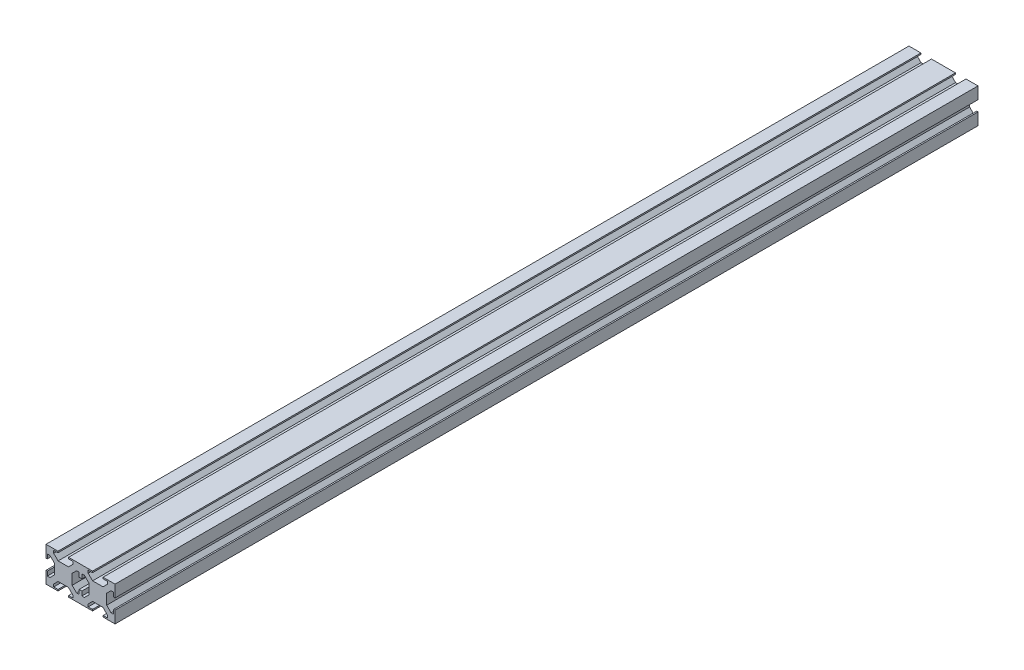
SolidWorks part; units mm, degrees
ref_plane "前视基准面" through (0, 0, 0) normal (0, 0, 1) x (1, 0, 0)
ref_plane "上视基准面" through (0, 0, 0) normal (0, 1, 0) x (1, 0, 0)
ref_plane "右视基准面" through (0, 0, 0) normal (1, 0, 0) x (0, 0, -1)
sketch "草图1" plane through (0, 0, 0) normal (0, 0, 1) x (1, 0, 0)
  line L0 (30, 10) -> (10, -10) construction
  line L1 (-10, -10) -> (30, -10)
  line L2 (-10, -10) -> (-10, 10)
  line L3 (-10, 10) -> (30, 10)
  line L4 (10, -10) -> (10, 10) construction
  line L5 (-10, -10) -> (10, 10) construction
  line L6 (-10, 10) -> (10, -10) construction
  line L7 (30, -10) -> (10, 10) construction
  line L8 (30, -10) -> (30, 10)
  line L9 (-3.05, 10) -> (-3.05, 9.2)
  line L10 (-3.05, 9.2) -> (-5.55, 9.2)
  line L11 (-5.55, 9.2) -> (-5.55, 7.7)
  line L12 (-5.55, 7.7) -> (-3, 5.15)
  line L13 (-3, 5.15) -> (3, 5.15)
  line L14 (0, -1000) -> (0, 49000) construction
  line L15 (-1000, 0) -> (49000, 0) construction
  line L16 (5.55, 7.7) -> (3, 5.15)
  line L17 (5.55, 9.2) -> (5.55, 7.7)
  line L18 (3.05, 9.2) -> (5.55, 9.2)
  line L19 (3.05, 10) -> (3.05, 9.2)
  line L20 (10, 3.05) -> (9.2, 3.05)
  line L21 (9.2, 3.05) -> (9.2, 5.55)
  line L22 (9.2, 5.55) -> (7.7, 5.55)
  line L23 (7.7, 5.55) -> (5.15, 3)
  line L24 (5.15, 3) -> (5.15, -3)
  line L25 (7.7, -5.55) -> (5.15, -3)
  line L26 (9.2, -5.55) -> (7.7, -5.55)
  line L27 (9.2, -3.05) -> (9.2, -5.55)
  line L28 (10, -3.05) -> (9.2, -3.05)
  line L29 (3.05, -10) -> (3.05, -9.2)
  line L30 (3.05, -9.2) -> (5.55, -9.2)
  line L31 (5.55, -9.2) -> (5.55, -7.7)
  line L32 (5.55, -7.7) -> (3, -5.15)
  line L33 (3, -5.15) -> (-3, -5.15)
  line L34 (-5.55, -7.7) -> (-3, -5.15)
  line L35 (-5.55, -9.2) -> (-5.55, -7.7)
  line L36 (-3.05, -9.2) -> (-5.55, -9.2)
  line L37 (-3.05, -10) -> (-3.05, -9.2)
  line L38 (-10, -3.05) -> (-9.2, -3.05)
  line L39 (-9.2, -3.05) -> (-9.2, -5.55)
  line L40 (-9.2, -5.55) -> (-7.7, -5.55)
  line L41 (-7.7, -5.55) -> (-5.15, -3)
  line L42 (-5.15, -3) -> (-5.15, 3)
  line L43 (-7.7, 5.55) -> (-5.15, 3)
  line L44 (-9.2, 5.55) -> (-7.7, 5.55)
  line L45 (-9.2, 3.05) -> (-9.2, 5.55)
  line L46 (-10, 3.05) -> (-9.2, 3.05)
  line L47 (30, 3.05) -> (29.2, 3.05)
  line L48 (29.2, 3.05) -> (29.2, 5.55)
  line L49 (29.2, 5.55) -> (27.7, 5.55)
  line L50 (27.7, 5.55) -> (25.15, 3)
  line L51 (25.15, -3) -> (25.15, 3)
  line L52 (27.7, -5.55) -> (25.15, -3)
  line L53 (29.2, -5.55) -> (27.7, -5.55)
  line L54 (29.2, -3.05) -> (29.2, -5.55)
  line L55 (30, -3.05) -> (29.2, -3.05)
  line L56 (23.05, -10) -> (23.05, -9.2)
  line L57 (23.05, -9.2) -> (25.55, -9.2)
  line L58 (25.55, -9.2) -> (25.55, -7.7)
  line L59 (25.55, -7.7) -> (23, -5.15)
  line L60 (17, -5.15) -> (23, -5.15)
  line L61 (14.45, -7.7) -> (17, -5.15)
  line L62 (14.45, -9.2) -> (14.45, -7.7)
  line L63 (16.95, -9.2) -> (14.45, -9.2)
  line L64 (16.95, -10) -> (16.95, -9.2)
  line L65 (10, -3.05) -> (10.8, -3.05)
  line L66 (10.8, -3.05) -> (10.8, -5.55)
  line L67 (10.8, -5.55) -> (12.3, -5.55)
  line L68 (12.3, -5.55) -> (14.85, -3)
  line L69 (14.85, 3) -> (14.85, -3)
  line L70 (12.3, 5.55) -> (14.85, 3)
  line L71 (10.8, 5.55) -> (12.3, 5.55)
  line L72 (10.8, 3.05) -> (10.8, 5.55)
  line L73 (10, 3.05) -> (10.8, 3.05)
  line L74 (16.95, 10) -> (16.95, 9.2)
  line L75 (16.95, 9.2) -> (14.45, 9.2)
  line L76 (14.45, 9.2) -> (14.45, 7.7)
  line L77 (14.45, 7.7) -> (17, 5.15)
  line L78 (23, 5.15) -> (17, 5.15)
  line L79 (25.55, 7.7) -> (23, 5.15)
  line L80 (25.55, 9.2) -> (25.55, 7.7)
  line L81 (23.05, 9.2) -> (25.55, 9.2)
  line L82 (23.05, 10) -> (23.05, 9.2)
  point P0 (0, 0)
  point P8 (20, 0)
  point P20 (0, 5.15)
  point P24 (25.15, 0)
  point P34 (5.15, 0)
  point P45 (0, -5.15)
  point P56 (-5.15, 0)
  point P60 (0, 0)
  point P72 (20, -5.15)
  point P83 (14.85, 0)
  point P94 (20, 5.15)
  point P105 (20, 0)
  dimension "D1" = 20
  dimension "D2" = 20
  dimension "D3" = 6
  dimension "D4" = 3.05
  dimension "D5" = 0.8
  dimension "D6" = 1.5
  dimension "D7" = 2.5
  dimension "D8" = 4
  dimension "D9" = 4
extrude "凸台-拉伸1" add sketch "草图1" along normal blind 500
